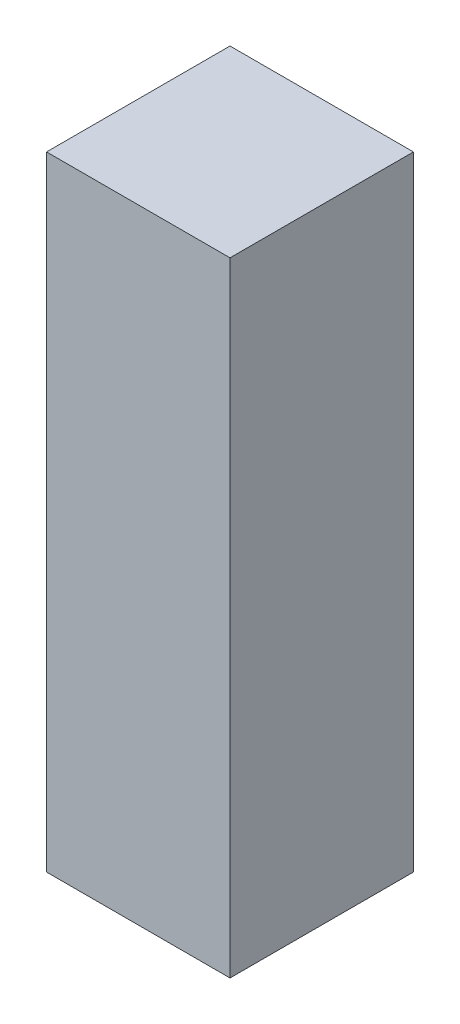
SolidWorks part; units mm, degrees
material "Balsa"
ref_plane "Alzado" through (0, 0, 0) normal (0, 0, 1) x (1, 0, 0)
ref_plane "Planta" through (0, 0, 0) normal (0, 1, 0) x (1, 0, 0)
ref_plane "Vista lateral" through (0, 0, 0) normal (1, 0, 0) x (0, 0, -1)
sketch "Croquis1" plane through (0, 0, 0) normal (0, 1, 0) x (1, 0, 0)
  line L1 (-2.5, -2.5) -> (2.5, -2.5)
  line L2 (-2.5, -2.5) -> (-2.5, 2.5)
  line L3 (-2.5, 2.5) -> (2.5, 2.5)
  line L4 (2.5, -2.5) -> (2.5, 2.5)
  line L5 (-2.5, -2.5) -> (2.5, 2.5) construction
  line L6 (-2.5, 2.5) -> (2.5, -2.5) construction
  point P0 (0, 0)
  dimension "D1" = 5
  dimension "D2" = 5
extrude "Saliente-Extruir1" add sketch "Croquis1" along normal mid plane 17
